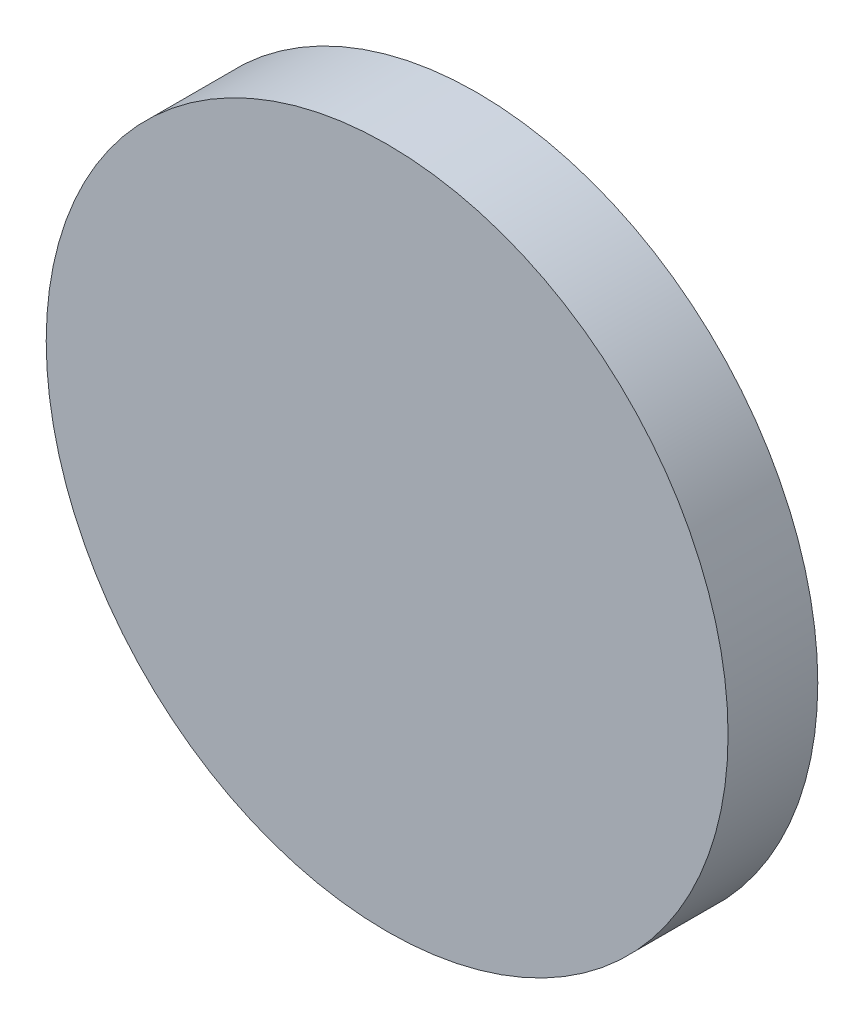
SolidWorks part; units mm, degrees
ref_plane "Front Plane" through (0, 0, 0) normal (0, 0, 1) x (1, 0, 0)
ref_plane "Top Plane" through (0, 0, 0) normal (0, 1, 0) x (1, 0, 0)
ref_plane "Right Plane" through (0, 0, 0) normal (1, 0, 0) x (0, 0, -1)
sketch "Sketch1" plane through (0, 0, 0) normal (0, 0, 1) x (1, 0, 0)
  line L0 (0, 10.3237) -> (0, -11.9962) construction
  circle A0 centre (0, 0) radius 19
  circle A1 centre (0, 0) radius 2 construction
  dimension "D1" = 4
  dimension "D2" = 38
extrude "Boss-Extrude1" add sketch "Sketch1" along normal blind 5
sketch "Sketch3" plane through (0, 0, 0) normal (0, 1, 0) x (1, 0, 0)
  line L0 (-14.5, 6.5) -> (-14.5, 0) construction
  line L1 (19, 0) -> (-19, 0) construction
  line L2 (-16.5, 6.5) -> (-16.5, 0)
  line L3 (-16.5, 0) -> (-14.5, 0)
  line L4 (-14.5, 0) -> (-14.5, 8.5)
  line L5 (-19, 0) -> (-19, -5) construction
  circle A0 centre (-14.5, 6.5) radius 2 construction
  arc A1 (-16.5, 6.5) -> (-14.5, 8.5) centre (-14.5, 6.5) cw
  dimension "D1" = 4
  dimension "D2" = 4.5
  dimension "D3" = 8.5
revolve "Revolve1" add sketch "Sketch3" angle 360 about L0
sketch "Sketch4" plane through (0, 0, 5) normal (0, 0, 1) x (1, 0, 0)
  line L0 (0, 0) -> (6.0417, 0)
